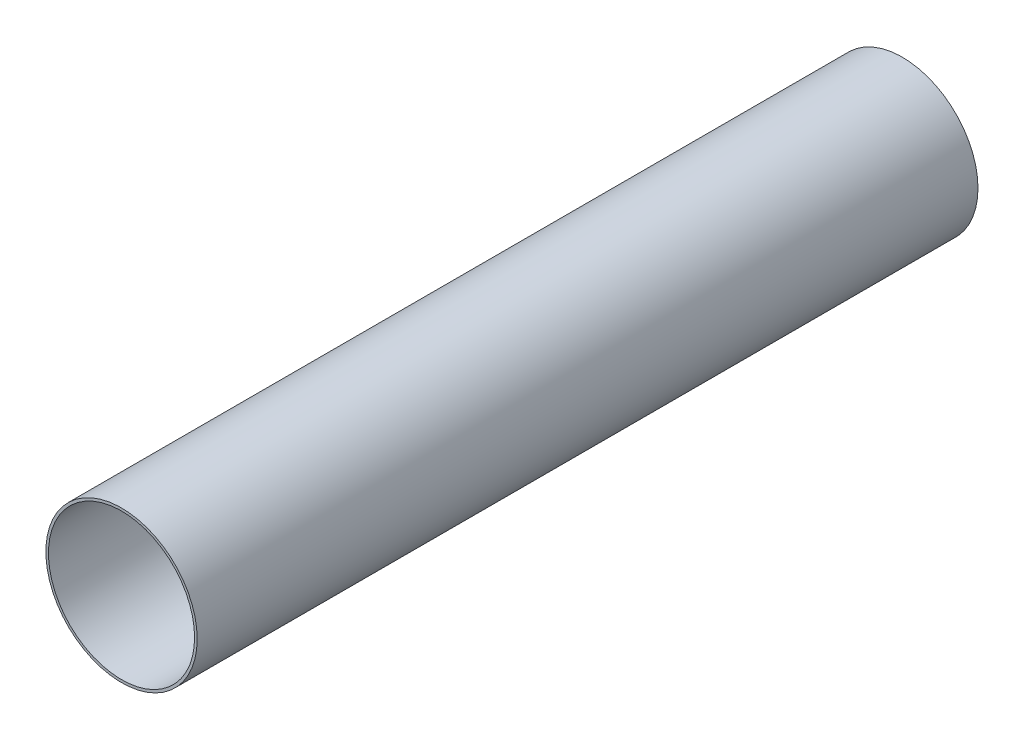
SolidWorks part; units mm, degrees
material "Acrílico (Impacto medio-alto)"
ref_plane "Alzado" through (0, 0, 0) normal (1, 0, 0) x (0, 1, 0)
ref_plane "Planta" through (0, 0, 0) normal (0, 0, 1) x (0, 1, 0)
ref_plane "Vista lateral" through (0, 0, 0) normal (0, 1, 0) x (-1, 0, 0)
sketch "Croquis1" plane through (0, 0, 0) normal (0, 0, 1) x (0, 1, 0)
  circle A0 centre (0, 0) radius 140.37
  circle A1 centre (0, 0) radius 145.37
  dimension "D1" = 280.74
  dimension "D2" = 5
extrude "Saliente-Extruir1" add sketch "Croquis1" along normal blind 1500
